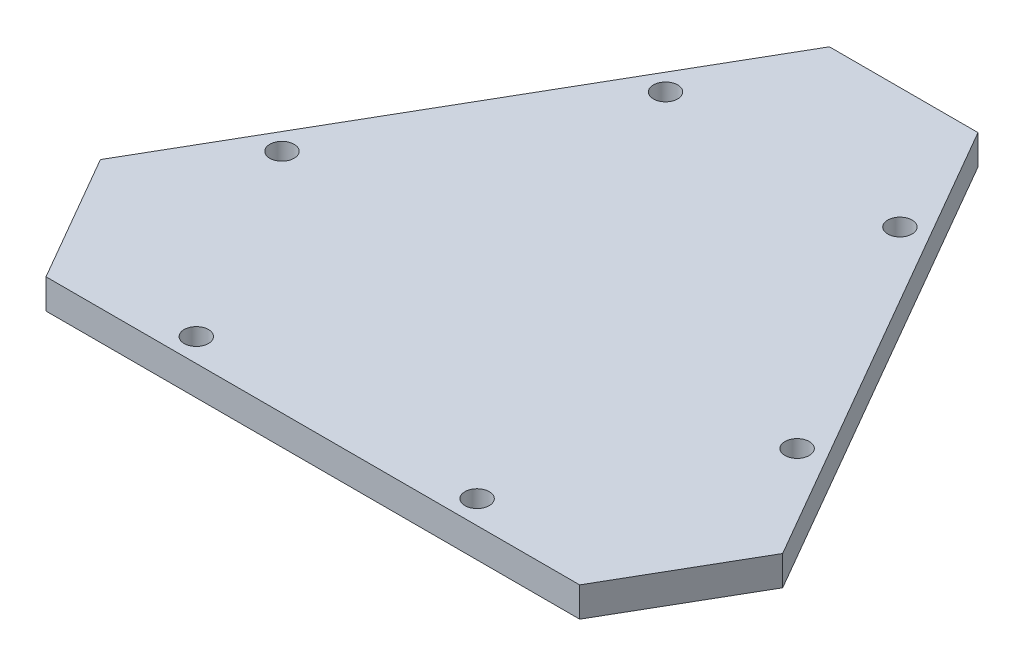
SolidWorks part; units mm, degrees
ref_plane "Front Plane" through (0, 0, 0) normal (0, 0, 1) x (1, 0, 0)
ref_plane "Top Plane" through (0, 0, 0) normal (0, 1, 0) x (1, 0, 0)
ref_plane "Right Plane" through (0, 0, 0) normal (1, 0, 0) x (0, 0, -1)
sketch "Sketch1" plane through (0, 0, 0) normal (0, 1, 0) x (1, 0, 0)
  line L0 (-64.9519, -37.5) -> (0, 0) construction
  line L1 (0, 0) -> (64.9519, -37.5) construction
  line L2 (0, 0) -> (0, 75) construction
  line L3 (-15.875, 75) -> (15.875, 75)
  line L4 (57.0144, -51.2482) -> (72.8894, -23.7518)
  line L5 (-57.0144, -51.2482) -> (-72.8894, -23.7518)
  line L6 (-15.875, 75) -> (-72.8894, -23.7518)
  line L7 (-57.0144, -51.2482) -> (57.0144, -51.2482)
  line L8 (72.8894, -23.7518) -> (15.875, 75)
  point P11 (64.9519, -37.5)
  point P12 (-64.9519, -37.5)
  dimension "D3" = 75
  dimension "D1" = 120
  dimension "D2" = 120
  dimension "D4" = 31.75
  dimension "D5" = 114.0288
  dimension "D6" = 114.0288
  dimension "D7" = 114.0288
extrude "Boss-Extrude1" add sketch "Sketch1" along normal blind 6.35
sketch "Sketch9" plane through (0, 6.35, 0) normal (0, 1, 0) x (1, 0, 0)
  line L0 (-25.0303, 49.1428) -> (-29.3414, 51.6755)
  line L1 (-15.875, 75) -> (-72.8894, -23.7518) construction
  line L2 (-55.0302, -2.8188) -> (-59.3603, -0.3188)
  line L10 (-15.875, 75) -> (-9.7477, 75)
  line L11 (15.875, 75) -> (-15.875, 75) construction
  line L13 (25.0086, 49.1802) -> (29.3387, 51.6802)
  line L14 (72.8894, -23.7518) -> (15.875, 75) construction
  line L16 (55.0087, -2.7812) -> (59.3603, -0.3188)
  line L20 (-29.9012, -46.2482) -> (-29.9012, -51.2482)
  line L21 (-57.0144, -51.2482) -> (57.0144, -51.2482) construction
  line L22 (30.0988, -46.2482) -> (30.0988, -51.2482)
  circle A0 centre (-29.9012, -46.2482) radius 2.6
  circle A1 centre (30.0988, -46.2482) radius 2.6
  circle A2 centre (25.0086, 49.1802) radius 2.6
  circle A4 centre (55.0087, -2.7812) radius 2.6
  circle A5 centre (-55.0302, -2.8188) radius 2.6
  circle A6 centre (-25.0303, 49.1428) radius 2.6
  dimension "D2" = 5
  dimension "D1" = 5.2
  dimension "D4" = 60
  dimension "D5" = 5.2
  dimension "D6" = 5.2
  dimension "D3" = 5
  dimension "D7" = 5.2
  dimension "D12" = 5.2
  dimension "D8" = 5
  dimension "D9" = 5
  dimension "D10" = 60
  dimension "D11" = 5
  dimension "D13" = 5
  dimension "D14" = 60
extrude "Cut-Extrude1" cut sketch "Sketch9" against normal through all contours A6 | A2 | A4 | A1 | A5 | A0
